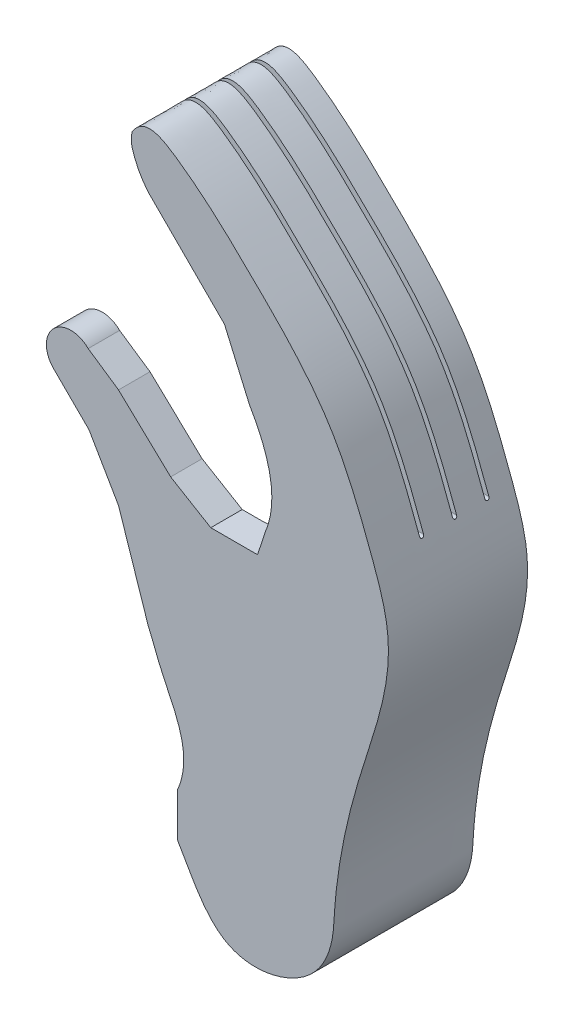
SolidWorks part; units mm, degrees
ref_plane "Front Plane" through (0, 0, 0) normal (0, 0, 1) x (1, 0, 0)
ref_plane "Top Plane" through (0, 0, 0) normal (0, 1, 0) x (1, 0, 0)
ref_plane "Right Plane" through (0, 0, 0) normal (1, 0, 0) x (0, 0, -1)
sketch "Sketch1" plane through (0, 0, 0) normal (0, 0, 1) x (1, 0, 0)
  line L0 (-32.4802, -164.0997) -> (-32.4802, -136.2085)
  line L1 (-69.7358, 63.0809) -> (-36.908, 32.0264)
  line L2 (-36.908, 32.0264) -> (-11.6444, 16.9607)
  line L3 (-11.6444, 16.9607) -> (17.8265, 16.9607)
  line L4 (-69.7358, 63.0809) -> (-88.8436, 76.049)
  line L5 (-69.7358, 0) -> (-51.108, -56.0007)
  line L6 (17.8265, 16.9607) -> (22.7532, 32.0264)
  line L7 (-110.6386, 54.2178) -> (-88.3235, 32.0264)
  line L8 (-51.108, 180.3607) -> (-15.7483, 145.0011)
  line L9 (-15.7483, 145.0011) -> (-3.0112, 132.2639)
  line L10 (-3.0112, 132.2639) -> (12.7463, 96.1804)
  line L19 (-88.3235, 32.0264) -> (-69.7358, 0)
  arc A0 (-88.8436, 76.049) -> (-110.6386, 54.2178) centre (-99.7411, 65.1334) ccw
  arc A1 (-61.1213, 208.2785) -> (-61.1213, 199.3049) centre (-42.265, 203.7917) ccw
  arc A2 (-61.1213, 199.3049) -> (-51.108, 180.3607) centre (-9.1743, 214.644) ccw
  spline S0 degree 3 poles (-32.4802, -164.0997) (-24.5253, -176.8207) (-6.9241, -218.8556) (54.3252, -203.4354) (65.3596, -171.9637) (67.2836, -130.144) (79.9018, -70.5536) (108.3704, 0.6418) (86.122, 62.4523) (64.1115, 117.3406) (15.4375, 165.6788) (-21.8732, 201.7553) (-53.198, 220.7872) (-61.1213, 208.2785) knots 0 0 0 0 0.089316 0.181586 0.234616 0.247739 0.393701 0.545483 0.610857 0.718682 0.844293 0.945226 1 1 1 1
  spline S1 degree 3 poles (-32.4802, -136.2085) (-21.6515, -110.9745) (-39.8706, -87.7742) (-48.8281, -60.9305) (-51.108, -56.0007) knots 0 0 0 0 0.610193 0.759721 0.759721 0.759721 0.759721
  spline S2 degree 2 poles (22.7532, 32.0264) (34.4074, 59.7737) (12.7463, 96.1804) knots 0 0 0 1 1 1
extrude "Boss-Extrude1" add sketch "Sketch1" along normal blind 87.63
sketch "Sketch2" plane through (0, 0, 0) normal (0, 0, 1) x (1, 0, 0)
  line L0 (17.8265, 16.9607) -> (-98.5287, 121.1114)
  line L1 (-98.5287, 121.1114) -> (-172.575, 58.2654)
  line L2 (-172.575, 58.2654) -> (-29.4902, -109.5458)
  arc A0 (17.8265, 16.9607) -> (-29.4902, -109.5458) centre (151.2561, -105.0475) ccw
  spline S0 degree 3 poles (-51.108, -56.0007) (-48.8281, -60.9305) (-39.8706, -87.7742) (-21.6515, -110.9745) (-32.4802, -136.2085) knots 0 0 0 0 0.149527 0.759721 0.759721 0.759721 0.759721 construction
extrude "Cut-Extrude1" cut sketch "Sketch2" along normal blind 67.818
sketch "Sketch3" plane through (0, 0, 0) normal (1, 0, 0) x (0, 0, -1)
  line L0 (-37.846, 225.8002) -> (-56.134, 225.8002)
  line L1 (-14.986, 225.8002) -> (-14.986, 48.8835)
  line L2 (0, -208.602) -> (0, 215.2954) construction
  line L3 (-17.526, 48.8835) -> (-17.526, 225.8002)
  line L5 (-17.526, 225.8002) -> (-35.306, 225.8002)
  line L6 (-35.306, 225.8002) -> (-35.306, 48.8835)
  line L8 (-37.846, 48.8835) -> (-37.846, 225.8002)
  line L9 (-56.134, 225.8002) -> (-56.134, 48.8835)
  line L11 (-58.674, 48.8835) -> (-58.674, 244.6169)
  line L12 (-58.674, 244.6169) -> (-14.986, 244.6169)
  line L13 (-14.986, 244.6169) -> (-14.986, 225.8002)
  arc A0 (-58.674, 48.8835) -> (-56.134, 48.8835) centre (-57.404, 48.8835) ccw
  arc A1 (-37.846, 48.8835) -> (-35.306, 48.8835) centre (-36.576, 48.8835) ccw
  arc A2 (-17.526, 48.8835) -> (-14.986, 48.8835) centre (-16.256, 48.8835) ccw
  dimension "D9" = 195.7334
  dimension "D10" = 244.6169
  dimension "D1" = 14.986
  dimension "D2" = 17.78
  dimension "D3" = 18.288
  dimension "D4" = 2.54
  dimension "D5" = 2.54
  dimension "D6" = 2.54
  dimension "D7" = 18.8167
  dimension "D8" = 18.8167
  dimension "D11" = 18.8167
  dimension "D12" = 48.8835
  dimension "D13" = 48.8835
sketch "Sketch5" plane through (0, 0, 0) normal (1, 0, 0) x (0, 0, -1)
  line L0 (-58.674, 244.6169) -> (-14.986, 244.6169) construction
  line L1 (-58.674, 48.8835) -> (-58.674, 244.6169) construction
  line L2 (-14.986, 244.6169) -> (-14.986, 225.8002) construction
  line L3 (-14.986, 225.8002) -> (-14.986, 48.8835) construction
  line L4 (-17.526, 48.8835) -> (-17.526, 225.8002) construction
  line L5 (-17.526, 225.8002) -> (-35.306, 225.8002) construction
  line L6 (-35.306, 225.8002) -> (-35.306, 48.8835) construction
  line L7 (-37.846, 48.8835) -> (-37.846, 225.8002) construction
  line L8 (-37.846, 225.8002) -> (-56.134, 225.8002) construction
  line L9 (-56.134, 225.8002) -> (-56.134, 48.8835) construction
  line L10 (-58.674, 244.6169) -> (-14.986, 244.6169) construction
  line L11 (-58.674, 48.8835) -> (-58.674, 244.6169) construction
  line L12 (-14.986, 244.6169) -> (-14.986, 225.8002) construction
  line L13 (-14.986, 225.8002) -> (-14.986, 48.8835) construction
  line L14 (-17.526, 48.8835) -> (-17.526, 225.8002) construction
  line L15 (-17.526, 225.8002) -> (-35.306, 225.8002) construction
  line L16 (-35.306, 225.8002) -> (-35.306, 48.8835) construction
  line L17 (-37.846, 48.8835) -> (-37.846, 225.8002) construction
  line L18 (-37.846, 225.8002) -> (-56.134, 225.8002) construction
  line L19 (-56.134, 225.8002) -> (-56.134, 48.8835) construction
  line L20 (-14.986, 244.6169) -> (-58.674, 244.6169)
  line L21 (-58.674, 244.6169) -> (-58.674, 85.1595)
  line L22 (-58.674, 85.1595) -> (-56.134, 85.1595)
  line L23 (-56.134, 85.1595) -> (-56.134, 225.8002)
  line L24 (-56.134, 225.8002) -> (-37.846, 225.8002)
  line L25 (-35.306, 85.1595) -> (-37.846, 85.1595)
  line L26 (-35.306, 85.1595) -> (-35.306, 225.8002)
  line L27 (-17.526, 225.8002) -> (-17.526, 85.1595)
  line L28 (-17.526, 85.1595) -> (-14.986, 85.1595)
  line L29 (-14.986, 85.1595) -> (-14.986, 244.6169)
  line L30 (-37.846, 85.1595) -> (-37.846, 225.8002)
  line L31 (-17.526, 225.8002) -> (-35.306, 225.8002)
  arc A0 (-58.674, 48.8835) -> (-56.134, 48.8835) centre (-57.404, 48.8835) ccw construction
  arc A1 (-37.846, 48.8835) -> (-35.306, 48.8835) centre (-36.576, 48.8835) ccw construction
  arc A2 (-17.526, 48.8835) -> (-14.986, 48.8835) centre (-16.256, 48.8835) ccw construction
  arc A3 (-58.674, 48.8835) -> (-56.134, 48.8835) centre (-57.404, 48.8835) ccw construction
  arc A4 (-37.846, 48.8835) -> (-35.306, 48.8835) centre (-36.576, 48.8835) ccw construction
  arc A5 (-17.526, 48.8835) -> (-14.986, 48.8835) centre (-16.256, 48.8835) ccw construction
extrude "Cut-Extrude3" cut sketch "Sketch3" along normal blind 198.12
extrude "Cut-Extrude5" cut sketch "Sketch5" against normal blind 79.248
fillet "Fillet2" radius 12.7 1 edges at (-18.0885, -41.7083, 67.818)
